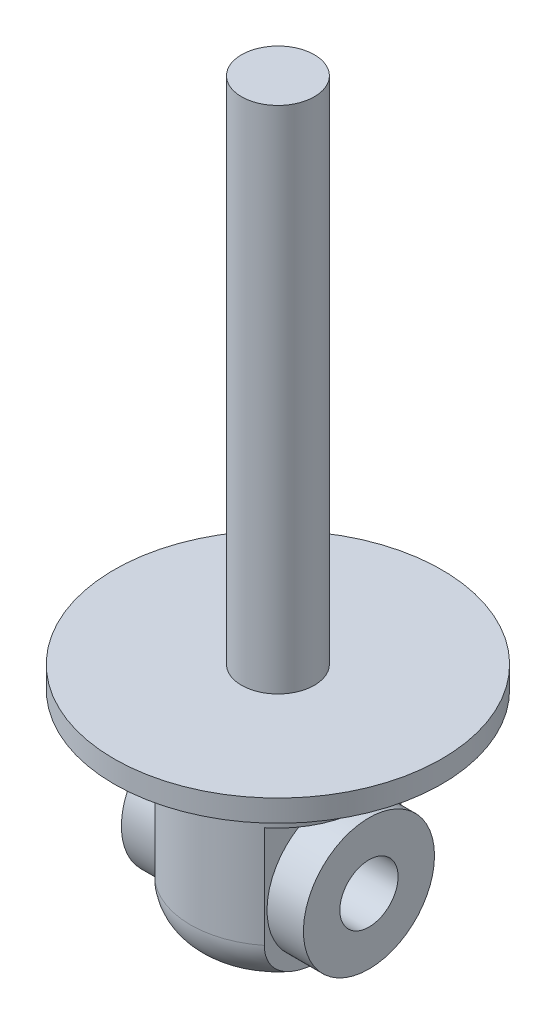
SolidWorks part; units mm, degrees
ref_plane "Front Plane" through (0, 0, 0) normal (0, 0, 1) x (1, 0, 0)
ref_plane "Top Plane" through (0, 0, 0) normal (0, 1, 0) x (1, 0, 0)
ref_plane "Right Plane" through (0, 0, 0) normal (1, 0, 0) x (0, 0, -1)
sketch "Sketch2" plane through (0, 0, 0) normal (0, 1, 0) x (1, 0, 0)
  circle A0 centre (0, 0) radius 22.5
  dimension "D1" = 45
extrude "Boss-Extrude1" add sketch "Sketch2" along normal blind 3 contours A0
sketch "Sketch3" plane through (0, 3, 0) normal (0, 1, 0) x (1, 0, 0)
  circle A0 centre (0, 0) radius 5
  dimension "D1" = 10
extrude "Boss-Extrude2" add sketch "Sketch3" along normal blind 70
sketch "Sketch4" plane through (0, 0, 0) normal (0, -1, 0) x (1, 0, 0)
  circle A0 centre (0, 0) radius 12
  dimension "D1" = 24
extrude "Boss-Extrude3" add sketch "Sketch4" along normal blind 28
fillet "Fillet1" radius 6 1 edges at (0, -28, -12)
sketch "Sketch5" plane through (0, 0, 0) normal (0, 0, 1) x (1, 0, 0)
  line L0 (0, 0) -> (0, -28) construction
  line L1 (-6, -28) -> (6, -28) construction
  line L2 (7.5, -28) -> (27.5, -28)
  line L3 (27.5, -28) -> (27.5, -8)
  line L4 (27.5, -8) -> (7.5, -8)
  line L5 (7.5, -8) -> (7.5, -28)
  line L6 (-7.5, -8) -> (-7.5, -28)
  line L7 (-27.5, -8) -> (-7.5, -8)
  line L8 (-27.5, -28) -> (-27.5, -8)
  line L9 (-7.5, -28) -> (-27.5, -28)
  dimension "D1" = 15
  dimension "D2" = 20
  dimension "D3" = 20
  dimension "D4" = 28
extrude "Cut-Extrude1" cut sketch "Sketch5" against normal through all both and the other way through all
sketch "Sketch6" plane through (7.5, 0, 0) normal (1, 0, 0) x (0, 0, -1)
  line L0 (0, -8) -> (0, -28) construction
  line L1 (-6, -28) -> (6, -28) construction
  line L2 (-9.3675, -8) -> (9.3675, -8) construction
  line L3 (-9.3675, -8) -> (9.3675, -8) construction
  circle A0 centre (0, -18) radius 4
  point P0 (0, 0)
  point P10 (0, -18)
  dimension "D1" = 8
extrude "Cut-Extrude2" cut sketch "Sketch6" against normal through all and the other way through all
sketch "Sketch7" plane through (0, 0, 0) normal (1, 0, 0) x (0, 0, -1)
  circle A0 centre (0, -18) radius 9
  circle A1 centre (0, -18) radius 4 construction
  circle A2 centre (0, -18) radius 4
  dimension "D1" = 18
extrude "Boss-Extrude4" add sketch "Sketch7" along normal mid plane 25
